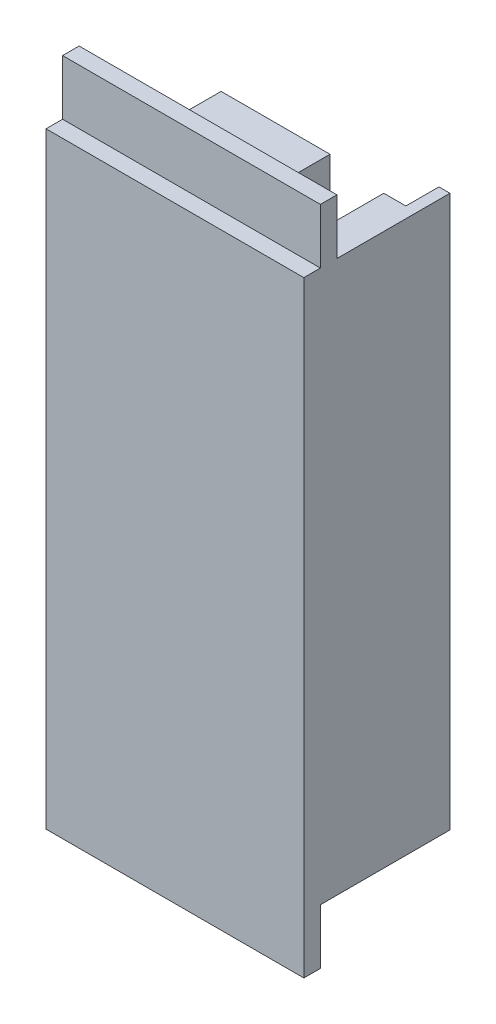
SolidWorks part; units mm, degrees
ref_plane "Front Plane" through (0, 0, 0) normal (0, 0, 1) x (1, 0, 0)
ref_plane "Top Plane" through (0, 0, 0) normal (0, 1, 0) x (1, 0, 0)
ref_plane "Right Plane" through (0, 0, 0) normal (1, 0, 0) x (0, 0, -1)
sketch "Sketch1" plane through (0, 0, 0) normal (0, 1, 0) x (1, 0, 0)
  line L15 (0, 0) -> (0, 6)
  line L18 (9.75, 0) -> (9.75, 6)
  line L19 (9.75, 6) -> (14.75, 6)
  line L20 (-5, 6) -> (0, 6)
  line L21 (-5, 6) -> (-5, 15.75)
  line L22 (-5, 15.75) -> (14.75, 15.75)
  line L23 (14.75, 6) -> (14.75, 15.75)
  line L24 (-15, 0) -> (0, 0)
  line L25 (-15, 0) -> (-15, -6)
  line L26 (-15, -6) -> (24.75, -6)
  line L28 (9.75, 0) -> (25.75, 0)
  line L29 (4.875, -6) -> (4.875, 15.75) construction
  line L30 (29.75, 20.5) -> (29.75, 14.5)
  line L31 (24.75, -6) -> (31.75, -6)
  line L32 (25.75, 0) -> (25.75, 14.5)
  line L33 (29.75, 20.5) -> (31.75, 20.5)
  line L34 (31.75, -6) -> (31.75, 20.5)
  line L35 (29.75, 14.5) -> (25.75, 14.5)
  line L36 (25.75, 14.5) -> (29.75, 14.5)
  dimension "D1" = 6
  dimension "D2" = 9.75
  dimension "D3" = 19.75
  dimension "D4" = 9.75
  dimension "D5" = 5
  dimension "D6" = 5
  dimension "D7" = 16
  dimension "D8" = 15
  dimension "D10" = 46.75
  dimension "D11" = 6
  dimension "D12" = 21.75
  dimension "D13" = 6
  dimension "D14" = 26.5
  dimension "D15" = 6
  dimension "D16" = 4
extrude "Boss-Extrude1" add sketch "Sketch1" along normal blind 100 contours L26 L29 L22 L21 L20 L15 L24 L25 | L29 L26 L31 L34 L33 L30 L35 L32 L28 L18 L19 L23 L22
sketch "Sketch2" plane through (0, 0, 0) normal (0, -1, 0) x (1, 0, 0)
  line L0 (31.75, 3) -> (-15, 3)
  line L1 (31.75, 6) -> (31.75, -20.5) construction
  line L2 (-15, 0) -> (-15, 6) construction
  line L3 (-15, 3) -> (-15, 6)
  line L4 (-15, 6) -> (31.75, 6)
  line L5 (31.75, 6) -> (31.75, 3)
  dimension "D1" = 3
extrude "Boss-Extrude2" add sketch "Sketch2" along normal blind 10
sketch "Sketch3" plane through (0, 100, 0) normal (0, 1, 0) x (1, 0, 0)
  line L0 (-15, -3) -> (31.75, -3)
  line L1 (-15, 0) -> (-15, -6) construction
  line L2 (31.75, -6) -> (31.75, 20.5) construction
  line L3 (31.75, -3) -> (31.75, 0)
  line L4 (31.75, 0) -> (-15, 0)
  line L5 (-15, 0) -> (-15, -3)
  dimension "D1" = 3
extrude "Boss-Extrude3" add sketch "Sketch3" along normal blind 10 contours L5 L0 L3 L4
